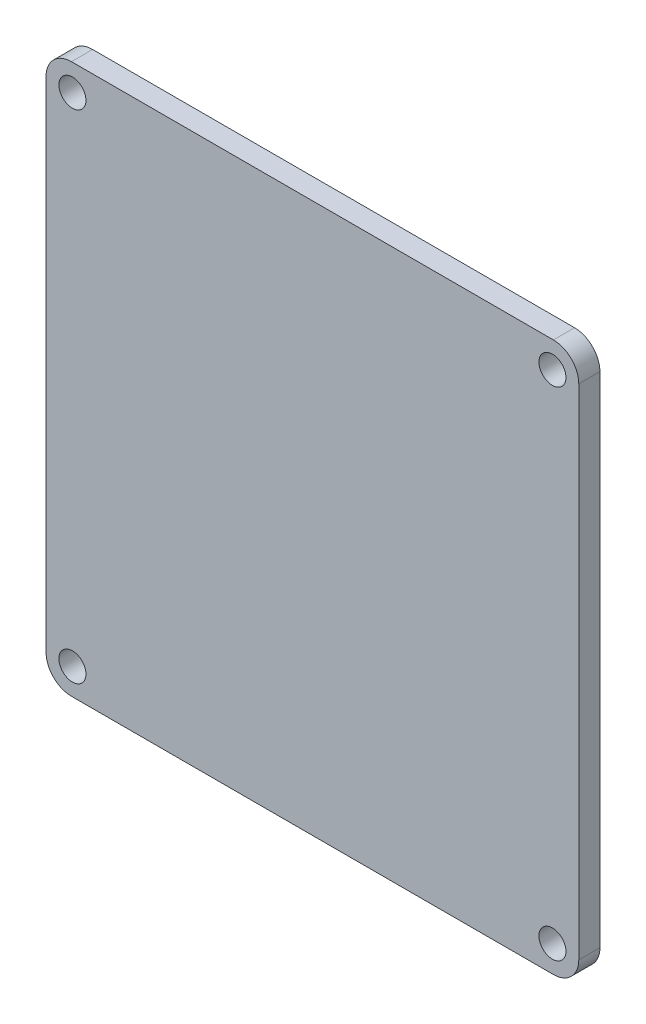
SolidWorks part; units mm, degrees
ref_plane "Front Plane" through (0, 0, 0) normal (0, 0, 1) x (1, 0, 0)
ref_plane "Top Plane" through (0, 0, 0) normal (0, 1, 0) x (1, 0, 0)
ref_plane "Right Plane" through (0, 0, 0) normal (1, 0, 0) x (0, 0, -1)
sketch "Sketch1" plane through (0, 0, 0) normal (0, 0, 1) x (1, 0, 0)
  line L1 (0, 0) -> (63, 0)
  line L2 (0, 0) -> (0, 65)
  line L3 (0, 65) -> (63, 65)
  line L4 (63, 0) -> (63, 65)
  line L5 (2.5, 62.5) -> (60.5, 62.5)
  line L6 (2.5, 62.5) -> (2.5, 2.5)
  line L7 (2.5, 2.5) -> (60.5, 2.5)
  line L8 (60.5, 62.5) -> (60.5, 2.5)
  line L9 (2.5, 54.5) -> (4.5, 54.5)
  line L10 (2.5, 54.5) -> (2.5, 51.5)
  line L11 (2.5, 51.5) -> (4.5, 51.5)
  line L12 (4.5, 54.5) -> (4.5, 51.5)
  line L21 (4.5, 35.5) -> (2.5, 35.5)
  line L22 (4.5, 35.5) -> (4.5, 38.5)
  line L23 (4.5, 38.5) -> (2.5, 38.5)
  line L24 (2.5, 35.5) -> (2.5, 38.5)
  line L25 (2.5, 33.4944) -> (60.5, 33.4944)
  line L26 (2.5, 33.4944) -> (2.5, 30.5)
  line L27 (2.5, 30.5) -> (60.5, 30.5)
  line L28 (60.5, 33.4944) -> (60.5, 30.5)
  circle A1 centre (6.75, 27) radius 2
  point P9 (31.5, 65)
  point P10 (31.5, 62.5)
  point P11 (0, 32.5)
  point P12 (2.5, 32.5)
  point P26 (3.5, 51.5)
  point P27 (3.5, 38.5)
  dimension "D10" = 4
  dimension "D1" = 63
  dimension "D2" = 58
  dimension "D3" = 65
  dimension "D4" = 60
  dimension "D5" = 8
  dimension "D6" = 3
  dimension "D7" = 2
  dimension "D8" = 3
  dimension "D9" = 28
  dimension "D11" = 3.5
  dimension "D12" = 2
  dimension "D13" = 24
  dimension "D14" = 0
  dimension "D15" = 4.25
extrude "Boss-Extrude3" add sketch "Sketch1" along normal blind 2.5 contours L2 L3 L4 L1
fillet "Fillet1" radius 3 4 edges at (63, 65, 1.25) (0, 65, 1.25) (0, 0, 1.25) (63, 0, 1.25)
sketch "Sketch2" plane through (0, 0, 0) normal (0, 0, 1) x (1, 0, 0)
  circle A0 centre (3.1155, 61.8845) radius 1.6
  circle A1 centre (59.8845, 61.8845) radius 1.6
  circle A2 centre (59.8845, 3.1155) radius 1.6
  circle A3 centre (3.1155, 3.1155) radius 1.6
  circle A4 centre (3.1155, 3.1155) radius 3.1155
  circle A5 centre (59.8845, 3.1155) radius 3.1155
  circle A6 centre (59.8845, 61.8845) radius 3.1155
  circle A7 centre (3.1155, 61.8845) radius 3.1155
  dimension "D1" = 3.2
  dimension "D2" = 3.2
  dimension "D3" = 3.2
  dimension "D4" = 3.2
  dimension "D9" = 6.231
  dimension "D10" = 6.231
  dimension "D11" = 6.231
  dimension "D12" = 6.231
extrude "Cut-Extrude13" cut sketch "Sketch2" along normal blind 2.5 contours A0 | A3 | A2 | A1
